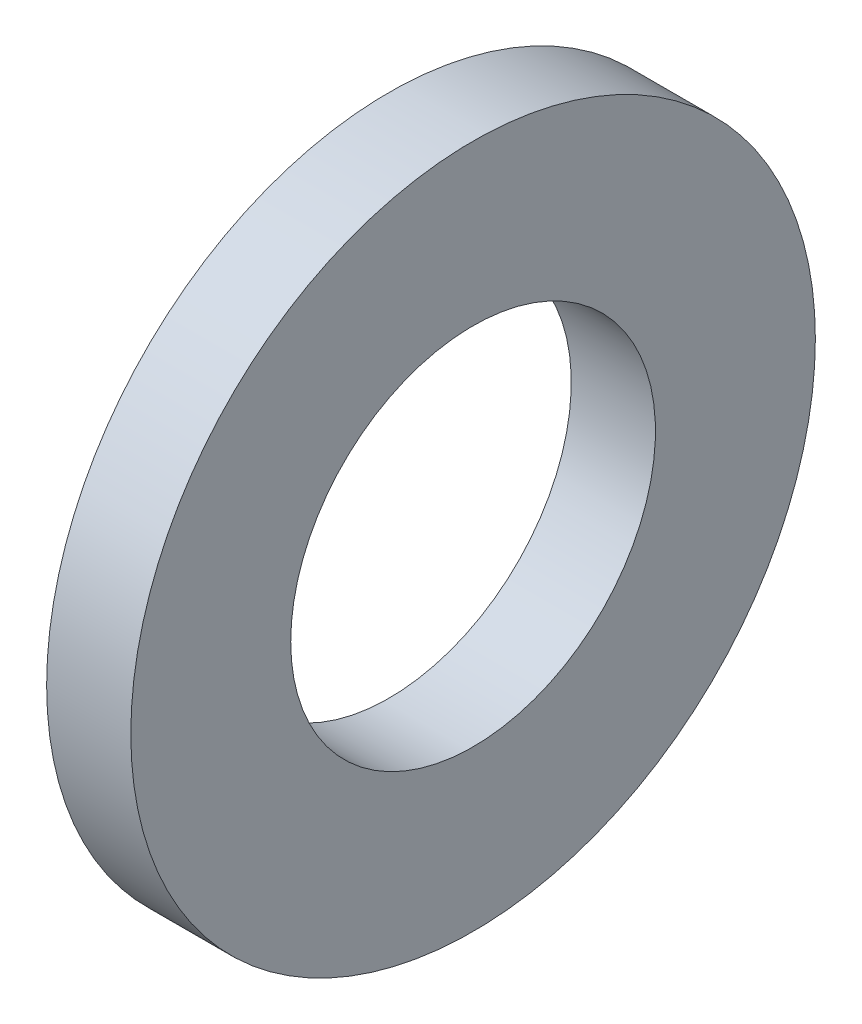
SolidWorks part; units mm, degrees
ref_plane "Front Plane" through (0, 0, 0) normal (0, 0, 1) x (1, 0, 0)
ref_plane "Top Plane" through (0, 0, 0) normal (0, 1, 0) x (1, 0, 0)
ref_plane "Right Plane" through (0, 0, 0) normal (1, 0, 0) x (0, 0, -1)
sketch "Sketch1" plane through (0, 0, 0) normal (0, 0, 1) x (1, 0, 0)
  line L0 (0, 0) -> (1.5, 0) construction
  line L1 (0, 3.25) -> (1.5, 3.25)
  line L2 (0, 3.25) -> (0, 6.1)
  line L3 (0, 6.1) -> (1.5, 6.1)
  line L4 (1.5, 3.25) -> (1.5, 6.1)
  dimension "FIX_2" = 12.2
  dimension "FIX_3" = 6.5
  dimension "FIX_1" = 1.5
revolve "Revolve1" add sketch "Sketch1" angle 360 about L0
